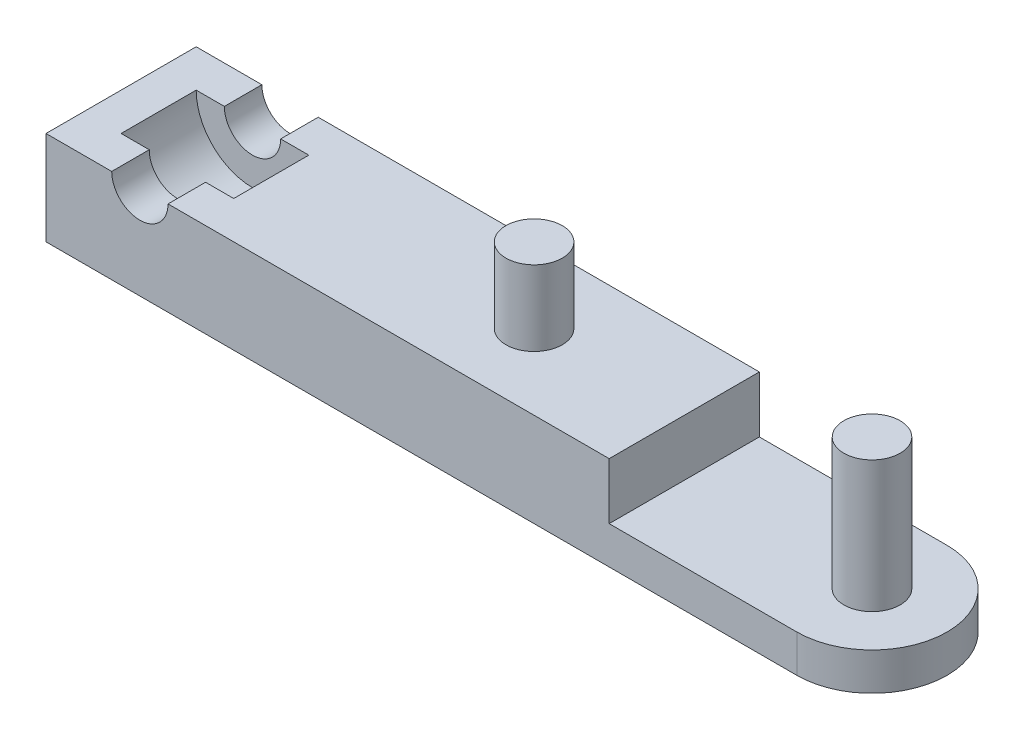
SolidWorks part; units mm, degrees
ref_plane "Front Plane" through (0, 0, 0) normal (0, 0, 1) x (1, 0, 0)
ref_plane "Top Plane" through (0, 0, 0) normal (0, 1, 0) x (1, 0, 0)
ref_plane "Right Plane" through (0, 0, 0) normal (1, 0, 0) x (0, 0, -1)
sketch "Sketch1" plane through (0, 0, 0) normal (0, 1, 0) x (1, 0, 0)
  line L0 (25, -4) -> (65, -4)
  line L1 (65, 4) -> (25, 4)
  line L2 (25, 4) -> (25, -4)
  arc A0 (65, -4) -> (65, 4) centre (65, 0) ccw
  dimension "D3" = 4
  dimension "D1" = 40
  dimension "D2" = 4
extrude "Boss-Extrude2" add sketch "Sketch1" along normal blind 2
sketch "Sketch3" plane through (0, 2, 0) normal (0, 1, 0) x (1, 0, 0)
  line L0 (25, -4) -> (65, -4) construction
  line L1 (25, 4) -> (55, 4)
  line L2 (25, 4) -> (25, -4)
  line L3 (25, -4) -> (55, -4)
  line L4 (55, 4) -> (55, -4)
  dimension "D1" = 30
extrude "Boss-Extrude3" add sketch "Sketch3" along normal blind 3
sketch "Sketch4" plane through (0, 2, 0) normal (0, 1, 0) x (1, 0, 0)
  circle A0 centre (65, 0) radius 1.5
  dimension "D1" = 3
extrude "Boss-Extrude4" add sketch "Sketch4" along normal blind 7
sketch "Sketch12" plane through (0, 5, 0) normal (0, 1, 0) x (1, 0, 0)
  line L0 (55, -4) -> (55, 4) construction
  circle A0 centre (47, 0) radius 1.5
  dimension "D1" = 3
  dimension "D2" = 8
extrude "Boss-Extrude6" add sketch "Sketch12" along normal blind 4
sketch "Sketch13" plane through (0, 0, 4) normal (0, 0, 1) x (1, 0, 0)
  line L0 (25, 5) -> (55, 5) construction
  line L1 (25, 5) -> (25, 0) construction
  line L2 (31.5, 5) -> (28.5, 5)
  arc A0 (31.5, 5) -> (28.5, 5) centre (30, 5) cw
  dimension "D1" = 1.5
  dimension "D2" = 5
extrude "Cut-Extrude1" cut sketch "Sketch13" against normal through all
sketch "Sketch14" plane through (0, 0, 0) normal (0, 0, 1) x (1, 0, 0)
  line L0 (25, 5) -> (28.5, 5) construction
  line L1 (31.5, 5) -> (55, 5) construction
  line L2 (27, 5) -> (33, 5)
  arc A0 (27, 5) -> (33, 5) centre (30, 5) ccw
  dimension "D1" = 3
extrude "Cut-Extrude2" cut sketch "Sketch14" against normal blind 2 and the other way blind 2
